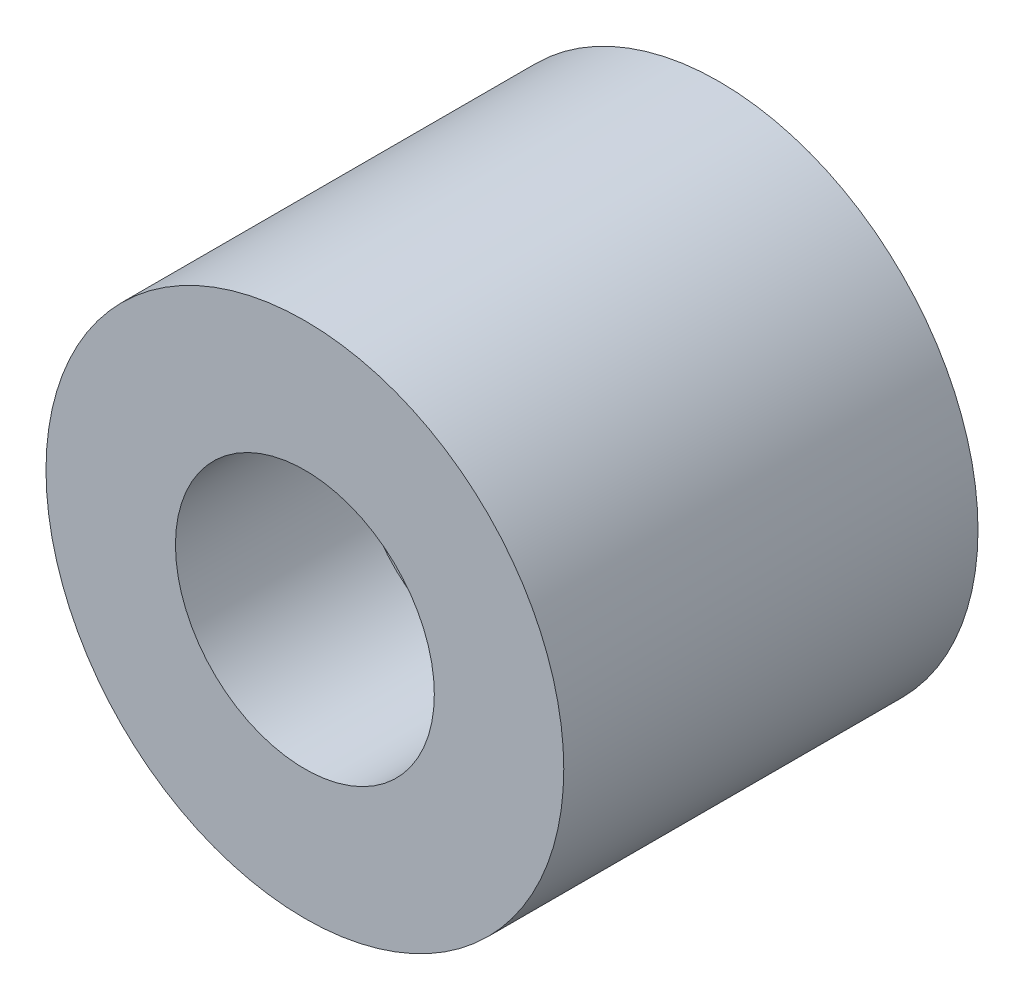
SolidWorks part; units mm, degrees
ref_plane "Front Plane" through (0, 0, 0) normal (0, 0, 1) x (1, 0, 0)
ref_plane "Top Plane" through (0, 0, 0) normal (0, 1, 0) x (1, 0, 0)
ref_plane "Right Plane" through (0, 0, 0) normal (1, 0, 0) x (0, 0, -1)
sketch "Sketch1" plane through (0, 0, 0) normal (0, 0, 1) x (1, 0, 0)
  circle A0 centre (0, 0) radius 6.35
extrude "Boss-Extrude1" add sketch "Sketch1" along normal blind 10.16
sketch "Sketch2" plane through (0, 0, 10.16) normal (0, 0, 1) x (1, 0, 0)
  circle A0 centre (0, 0) radius 3.175
extrude "Cut-Extrude1" cut sketch "Sketch2" against normal blind 4.445
sketch "Sketch3" plane through (0, 0, 0) normal (0, 0, -1) x (-1, 0, 0)
  circle A0 centre (0, 0) radius 2.921
extrude "Cut-Extrude2" cut sketch "Sketch3" against normal blind 4.445
